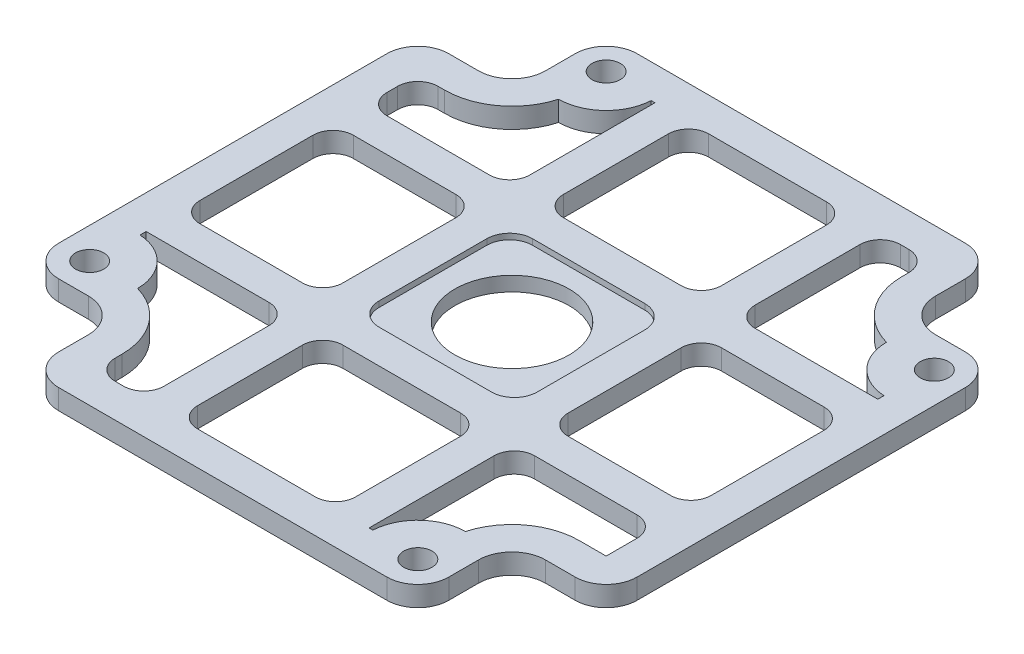
SolidWorks part; units mm, degrees
ref_plane "Front Plane" through (0, 0, 0) normal (0, 0, 1) x (1, 0, 0)
ref_plane "Top Plane" through (0, 0, 0) normal (0, 1, 0) x (1, 0, 0)
ref_plane "Right Plane" through (0, 0, 0) normal (1, 0, 0) x (0, 0, -1)
sketch "Sketch1" plane through (0, 0, 0) normal (0, 1, 0) x (1, 0, 0)
  line L1 (-43, -43) -> (43, -43)
  line L2 (-43, -43) -> (-43, 43)
  line L3 (-43, 43) -> (43, 43)
  line L4 (43, -43) -> (43, 43)
  line L5 (-43, -43) -> (43, 43) construction
  line L6 (-43, 43) -> (43, -43) construction
  point P0 (0, 0)
  dimension "D1" = 86
  dimension "D2" = 86
extrude "Boss-Extrude1" add sketch "Sketch1" along normal blind 3
sketch "Sketch2" plane through (0, 3, 0) normal (0, 1, 0) x (1, 0, 0)
  line L0 (29, 43) -> (29, 29)
  line L1 (-43, 43) -> (-29, 43)
  line L2 (-43, 43) -> (-43, 29)
  line L3 (-43, 29) -> (-29, 29)
  line L4 (-29, 43) -> (-29, 29)
  line L5 (29, 43) -> (43, 43)
  line L6 (43, 43) -> (43, 29)
  line L7 (29, 29) -> (43, 29)
  line L8 (29, -29) -> (29, -43)
  line L9 (29, -29) -> (43, -29)
  line L10 (43, -29) -> (43, -43)
  line L11 (29, -43) -> (43, -43)
  line L12 (-43, -29) -> (-43, -43)
  line L13 (-43, -29) -> (-29, -29)
  line L14 (-29, -29) -> (-29, -43)
  line L15 (-43, -43) -> (-29, -43)
  circle A0 centre (0, 0) radius 8.5
  point P15 (0, 0)
  dimension "D1" = 17
  dimension "D2" = 14
  dimension "D3" = 14
  dimension "D4" = 2
  dimension "D5" = 2
extrude "Cut-Extrude1" cut sketch "Sketch2" against normal through all
fillet "Fillet1" radius 4.6 8 edges at (29, 1.5, 43) (-43, 1.5, -29) (-43, 1.5, 29) (-29, 1.5, 43) (43, 1.5, 29) (43, 1.5, -29) (29, 1.5, -43) (-29, 1.5, -43)
fillet "Fillet2" radius 5 4 edges at (29, 1.5, -29) (-29, 1.5, -29) (-29, 1.5, 29) (29, 1.5, 29)
sketch "Sketch3" plane through (0, 3, 0) normal (0, 1, 0) x (1, 0, 0)
  circle A1 centre (38.4, 24.4) radius 2.1
  circle A2 centre (-24.4, 38.4) radius 2.1
  circle A3 centre (24.4, -38.4) radius 2.1
  circle A4 centre (-38.4, -24.4) radius 2.1
  dimension "D1" = 4.2
  dimension "D2" = 4.2
  dimension "D3" = 4.2
  dimension "D4" = 4.2
extrude "Cut-Extrude2" cut sketch "Sketch3" against normal through all
sketch "Sketch4" plane through (0, 3, 0) normal (0, 1, 0) x (1, 0, 0)
  line L1 (11.75, -11.4) -> (-11.75, -11.4)
  line L2 (11.75, -11.4) -> (11.75, 11.4)
  line L3 (11.75, 11.4) -> (-11.75, 11.4)
  line L4 (-11.75, -11.4) -> (-11.75, 11.4)
  line L5 (11.75, -11.4) -> (-11.75, 11.4) construction
  line L6 (11.75, 11.4) -> (-11.75, -11.4) construction
  circle A0 centre (0, 0) radius 8.5
  point P0 (0, 0)
  dimension "D3" = 17
  dimension "D1" = 23.5
  dimension "D2" = 22.8
extrude "Cut-Extrude3" cut sketch "Sketch4" against normal blind 0.85
fillet "Fillet3" radius 3.4 4 edges at (-11.75, 2.575, 11.4) (11.75, 2.575, 11.4) (11.75, 2.575, -11.4) (-11.75, 2.575, -11.4)
sketch "Sketch5" plane through (0, 3, 0) normal (0, 1, 0) x (1, 0, 0)
  line L0 (11.75, -8) -> (11.75, 8) construction
  line L1 (-38, -11.4) -> (-16.75, -11.4)
  line L2 (-38, -11.4) -> (-38, 11.4)
  line L3 (-38, 11.4) -> (-16.75, 11.4)
  line L4 (-16.75, -11.4) -> (-16.75, 11.4)
  line L5 (-38, -11.4) -> (-16.75, 11.4) construction
  line L6 (-38, 11.4) -> (-16.75, -11.4) construction
  line L7 (-11.75, 16.4) -> (11.75, 16.4)
  line L8 (-11.75, 16.4) -> (-11.75, 38)
  line L9 (-11.75, 38) -> (11.75, 38)
  line L10 (11.75, 16.4) -> (11.75, 38)
  line L11 (-11.75, 16.4) -> (11.75, 38) construction
  line L12 (-11.75, 38) -> (11.75, 16.4) construction
  line L13 (16.75, -11.4) -> (38, -11.4)
  line L14 (16.75, -11.4) -> (16.75, 11.4)
  line L15 (16.75, 11.4) -> (38, 11.4)
  line L16 (38, -11.4) -> (38, 11.4)
  line L17 (16.75, -11.4) -> (38, 11.4) construction
  line L18 (16.75, 11.4) -> (38, -11.4) construction
  line L19 (-11.75, -16.4) -> (11.75, -16.4)
  line L20 (-11.75, -16.4) -> (-11.75, -38)
  line L21 (-11.75, -38) -> (11.75, -38)
  line L22 (11.75, -16.4) -> (11.75, -38)
  line L23 (-11.75, -16.4) -> (11.75, -38) construction
  line L24 (-11.75, -38) -> (11.75, -16.4) construction
  line L25 (8.35, 11.4) -> (-8.35, 11.4) construction
  line L26 (-43, 24.4) -> (-43, -24.4) construction
  line L27 (-11.75, 8) -> (-11.75, -8) construction
  line L28 (43, -24.4) -> (43, 24.4) construction
  line L29 (8.35, 11.4) -> (-8.35, 11.4) construction
  line L30 (24.4, 43) -> (-24.4, 43) construction
  line L31 (-8.35, -11.4) -> (8.35, -11.4) construction
  line L32 (-24.4, -43) -> (24.4, -43) construction
  line L33 (-24, 43) -> (-24, -43)
  line L34 (-38, 38) -> (-16.75, 38)
  line L35 (-38, 38) -> (-38, 16.4)
  line L36 (-38, 16.4) -> (-16.75, 16.4)
  line L37 (-16.75, 38) -> (-16.75, 16.4)
  line L38 (-38, 38) -> (-16.75, 16.4) construction
  line L39 (-38, 16.4) -> (-16.75, 38) construction
  line L40 (-38, -38) -> (-16.75, -38)
  line L41 (-38, -38) -> (-38, -16.4)
  line L42 (-38, -16.4) -> (-16.75, -16.4)
  line L43 (-16.75, -38) -> (-16.75, -16.4)
  line L44 (-38, -38) -> (-16.75, -16.4) construction
  line L45 (-38, -16.4) -> (-16.75, -38) construction
  line L46 (38, -38) -> (16.75, -38)
  line L47 (38, -38) -> (38, -16.4)
  line L48 (38, -16.4) -> (16.75, -16.4)
  line L49 (16.75, -38) -> (16.75, -16.4)
  line L50 (38, -38) -> (16.75, -16.4) construction
  line L51 (38, -16.4) -> (16.75, -38) construction
  line L52 (38, 16.4) -> (16.75, 16.4)
  line L53 (38, 16.4) -> (38, 38)
  line L54 (38, 38) -> (16.75, 38)
  line L55 (16.75, 16.4) -> (16.75, 38)
  line L56 (38, 16.4) -> (16.75, 38) construction
  line L57 (38, 38) -> (16.75, 16.4) construction
  line L58 (24, 43) -> (24, -43)
  line L59 (43, -24) -> (-43, -24)
  line L60 (-43, 24) -> (43, 24)
  line L61 (-29, 34) -> (-29, 38.4) construction
  line L62 (-38.4, 29) -> (-34, 29) construction
  line L63 (29, 38.4) -> (29, 34) construction
  line L64 (38.4, -29) -> (34, -29) construction
  circle A0 centre (-24.4, 38.4) radius 7.1
  circle A1 centre (38.4, 24.4) radius 7.1
  circle A2 centre (24.4, -38.4) radius 7.1
  circle A3 centre (-38.4, -24.4) radius 7.1
  circle A8 centre (-24.4, 38.4) radius 2.1 construction
  circle A11 centre (38.4, 24.4) radius 2.1 construction
  circle A16 centre (24.4, -38.4) radius 2.1 construction
  circle A18 centre (-38.4, -24.4) radius 2.1 construction
  circle A20 centre (34, 34) radius 10
  circle A21 centre (-34, 34) radius 10
  circle A22 centre (-34, -34) radius 10
  circle A23 centre (34, -34) radius 10
  point P0 (-27.375, 0)
  point P5 (0, 27.2)
  point P10 (27.375, 0)
  point P15 (0, -27.2)
  point P20 (-27.375, -27.2)
  point P41 (-27.375, 27.2)
  point P49 (27.375, -27.2)
  point P54 (27.375, 27.2)
  dimension "D9" = 5
  dimension "D10" = 5
  dimension "D11" = 5
  dimension "D12" = 5
  dimension "D1" = 5
  dimension "D2" = 5
  dimension "D3" = 5
  dimension "D4" = 5
  dimension "D5" = 5
  dimension "D6" = 5
  dimension "D7" = 5
  dimension "D8" = 5
  dimension "D13" = 5
  dimension "D14" = 5
  dimension "D15" = 5
  dimension "D16" = 5
extrude "Cut-Extrude4" cut sketch "Sketch5" against normal through all contours L8 L60 L10 L9 | L60 L8 L7 L10 | L33 L3 L2 L1 | L3 L33 L1 L4 | L15 L58 L13 L16 | L58 L15 L14 L13 | L59 L22 L19 L20 | L22 L59 L20 L21 | L59 L58 L48 L49 | L59 L47 L48 L58 | A2 L58 L59 L49 L46 | A23 L59 L58 A2 | L43 L59 L33 L40 | L59 L43 L42 L33 | A3 L59 L33 L42 L41 | A22 L33 L59 A3 | L60 L35 L36 L33 | A0 L33 L60 L37 L34 | L60 L33 L36 L37 | A21 L60 L33 A0 | L55 L60 L58 L54 | L60 L55 L52 L58 | A1 L60 L58 L52 L53 | A20 L58 L60 A1
fillet "Fillet4" radius 3 27 edges at (-16.75, 1.5, -11.4) (-38, 1.5, -11.4) (-16.75, 1.5, 11.4) (-38, 1.5, 11.4) (-24, 1.5, 38) (-16.75, 1.5, 38) (-16.75, 1.5, 16.4) (-11.75, 1.5, 38) (11.75, 1.5, 38) (11.75, 1.5, 16.4) (-11.75, 1.5, 16.4) (38, 1.5, 16.4) (16.75, 1.5, 16.4) (38, 1.5, 11.4) (16.75, 1.5, 11.4) (16.75, 1.5, -11.4) (38, 1.5, -11.4) (-38, 1.5, -24) (-38, 1.5, -16.4) (24, 1.5, -38) (16.75, 1.5, -38) (11.75, 1.5, -38) (-11.75, 1.5, -38) (16.75, 1.5, -16.4) (11.75, 1.5, -16.4) (-11.75, 1.5, -16.4) (-16.75, 1.5, -16.4)
